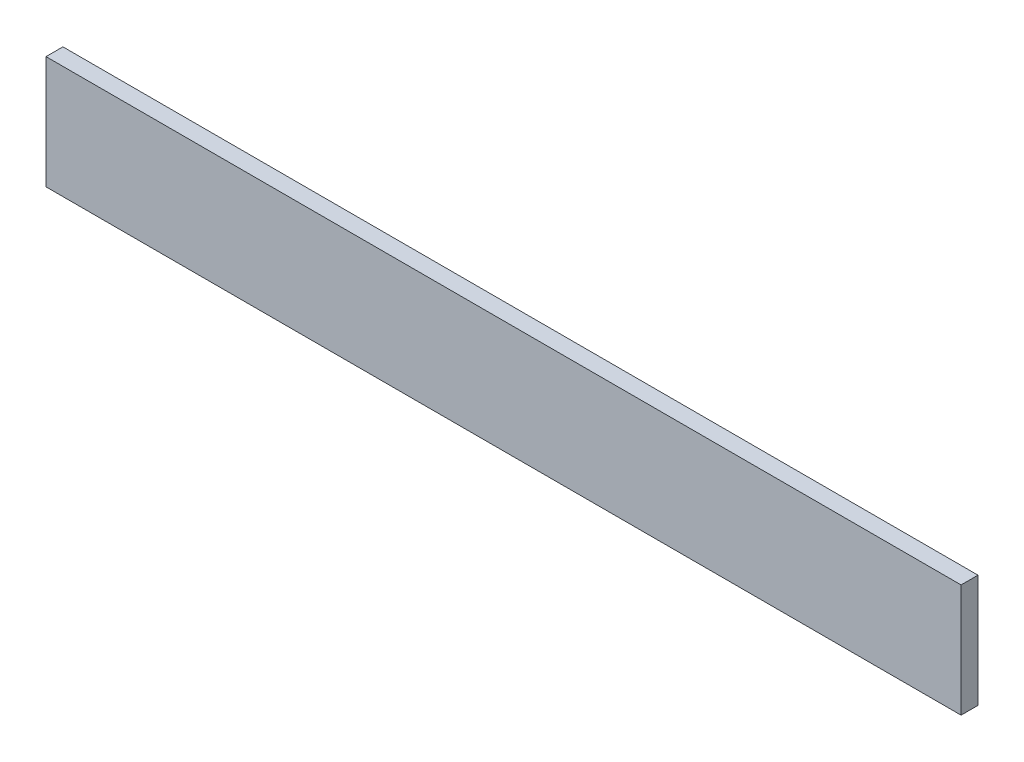
SolidWorks part; units mm, degrees
ref_plane "Alzado" through (0, 0, 0) normal (0, 0, 1) x (1, 0, 0)
ref_plane "Planta" through (0, 0, 0) normal (0, 1, 0) x (1, 0, 0)
ref_plane "Vista lateral" through (0, 0, 0) normal (1, 0, 0) x (0, 0, -1)
sketch "Croquis1" plane through (0, 0, 0) normal (0, 0, 1) x (1, 0, 0)
  line L0 (-405.6, 50) -> (405.6, 50)
  line L1 (-405.6, -50) -> (405.6, -50)
  line L2 (-405.6, -50) -> (-405.6, 50)
  line L4 (405.6, -50) -> (405.6, 50)
  line L5 (-405.6, -50) -> (405.6, 50) construction
  line L6 (-405.6, 50) -> (405.6, -50) construction
  point P0 (0, 0)
  dimension "D1" = 811.2
  dimension "D2" = 100
extrude "Saliente-Extruir1" add sketch "Croquis1" along normal blind 15
sketch "Croquis2" plane through (0, 0, 15) normal (0, 0, 1) x (1, 0, 0)
  line L0 (0, -50) -> (0, 50) construction
  line L1 (-405.6, -50) -> (405.6, -50) construction
  line L2 (405.6, 50) -> (-405.6, 50) construction
  line L3 (-405.6, 0) -> (405.6, 0) construction
  line L4 (-405.6, 50) -> (-405.6, -50) construction
  line L5 (405.6, -50) -> (405.6, 50) construction
sketch "Croquis3" plane through (0, 50, 0) normal (0, 1, 0) x (1, 0, 0)
  line L0 (0, -15) -> (0, 0) construction
  line L1 (405.6, 0) -> (-405.6, 0) construction
